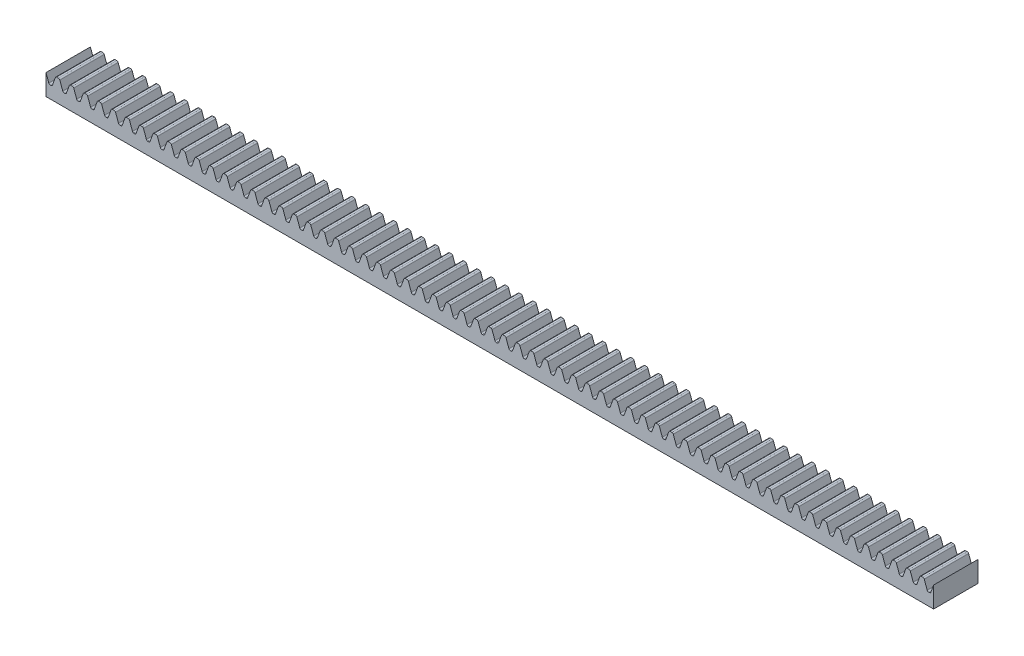
SolidWorks part; units mm, degrees
ref_plane "Front Plane" through (0, 0, 0) normal (0, 0, 1) x (1, 0, 0)
ref_plane "Top Plane" through (0, 0, 0) normal (0, 1, 0) x (1, 0, 0)
ref_plane "Right Plane" through (0, 0, 0) normal (1, 0, 0) x (0, 0, -1)
sketch "Sketch1" plane through (0, 0, 0) normal (0, 0, 1) x (1, 0, 0)
  line L0 (-50, 6) -> (-50, -6) construction
  line L1 (-50, -6) -> (50, -6) construction
  line L2 (50, -6) -> (50, 6) construction
  line L4 (0, 6) -> (0, -6) construction
  line L5 (-50, 5.5) -> (50, 5.5) construction
  line L6 (-48.9054, 6) -> (-48.484, 6) construction
  line L7 (-48.484, 6) -> (-48.0745, 4.875) construction
  line L8 (-48.9054, 6) -> (-49.3149, 4.875) construction
  line L9 (-49.3149, 4.875) -> (-48.0745, 4.875) construction
  line L10 (-48.6947, 6) -> (-48.6947, 4.875) construction
  line L11 (-50, 0) -> (-45.5531, 0) construction
  line L12 (50, 0) -> (45.5531, 0) construction
  point P15 (-47.1239, 6)
  point P16 (-31.5, -6)
  point P17 (-48.302, 5.5)
  point P18 (-49.0874, 5.5)
  point P21 (-0.25, -6)
  dimension "Length" = 100
  dimension "Height" = 12
  dimension "Approximate Number of Teeth" = 63
  dimension "Pressure Angle" = 20
  dimension "Circular Pitch" = 1.5708
  dimension "Addendum" = 0.5
  dimension "Dedendum" = 0.625
  dimension "Circular Tooth Thickness" = 0.7854
  dimension "Module" = 0.5
  dimension "Rack Length" = 97.3894
  dimension "D1" = 3.1416
sketch "Sketch2" plane through (0, 0, 0) normal (1, 0, 0) x (0, 0, -1)
  line L0 (-2.5, 0) -> (2.5, 0) construction
  dimension "Face Width" = 5
sketch "Sketch3" plane through (0, 0, 0) normal (0, 0, 1) x (1, 0, 0)
  line L1 (-50, 6) -> (50, 6)
  line L2 (-50, 6) -> (-50, -6)
  line L3 (-50, -6) -> (50, -6)
  line L4 (50, 6) -> (50, -6)
extrude "Boss-Extrude1" add sketch "Sketch3" against normal up to vertex (2.5 mm away) and the other way up to vertex (2.5 mm away) up to point (0, 0, -2.5) other way up to point (0, 0, 2.5)
sketch "Sketch4" plane through (0, 0, 0) normal (0, 0, 1) x (1, 0, 0)
  line L0 (-48.6947, 6) -> (-47.1239, 6) construction
  line L9 (-47.9093, 6) -> (-47.9093, 4.875)
  line L10 (-47.9093, 4.875) -> (-48.0745, 4.875)
  line L11 (-48.0745, 4.875) -> (-48.484, 6)
  line L12 (-48.484, 6) -> (-47.9093, 6)
  line L13 (-48.9054, 6) -> (-49.3149, 4.875)
  line L14 (-49.3149, 4.875) -> (-49.4801, 4.875)
  line L15 (-49.4801, 4.875) -> (-49.4801, 6)
  line L16 (-49.4801, 6) -> (-48.9054, 6)
  line L17 (50, 6) -> (-50, 6) construction
  line L18 (-48.9054, 6) -> (-48.7879, 6)
  line L19 (-48.6014, 6) -> (-48.484, 6)
  arc A0 (-49.4323, 4.875) -> (-49.2747, 4.9854) centre (-49.4323, 5.0428) ccw
  arc A1 (-48.1147, 4.9854) -> (-47.957, 4.875) centre (-47.957, 5.0428) ccw
  arc A2 (-48.9456, 5.8896) -> (-48.7879, 6) centre (-48.7879, 5.8322) cw
  arc A3 (-48.6014, 6) -> (-48.4438, 5.8896) centre (-48.6014, 5.8322) cw
  dimension "D1" = 0.1678
extrude "Cut-Extrude1" cut sketch "Sketch4" against normal through all both and the other way through all contours L14 A0 L13 L16 L15 | L13 A2 L18 | L19 A3 L11 | L11 A1 L10 L9 L12
pattern_linear "LPattern1" count 64 spacing 1.5708 along (1, 0, 0) count 2 spacing 1.5708 along (-1, 0, 0) of "Cut-Extrude1"
sketch "Drawing Refernce 1" plane through (0, 0, 2.5) normal (0, 0, 1) x (1, 0, 0)
  line L0 (-50, 0) -> (50, 0) construction
  point P6 (-35, 0)
  point P7 (-27.5, 0)
  point P8 (35, 0)
  dimension "D1" = 15
  dimension "D2" = 22.5
  dimension "D3" = 15
sketch "Sketch5" plane through (0, 0, 2.5) normal (0, 0, 1) x (1, 0, 0)
  line L0 (50, -6) -> (50, 5.8495) construction
  line L1 (-50, -6) -> (50, -6)
  line L2 (-50, -6) -> (-50, 3.5)
  line L3 (-50, 3.5) -> (50, 3.5)
  line L4 (50, -6) -> (50, 3.5)
  dimension "D1" = 2.5
extrude "Cut-Extrude2" cut sketch "Sketch5" against normal through all
equation "\"Diametral Pitch\"= 1 / \"Module\""
equation "\"Pressure Angle\"=20"
equation "\"Dedendum\"= 1.25 / \"Diametral Pitch\""
equation "\"Addendum\"= 1 / \"Diametral Pitch\""
equation "\"WorkingDepth\"= 2 / \"Diametral Pitch\""
equation "\"WholeDepth\"= 2.25 / \"Diametral Pitch\""
equation "\"Clearance\"= 0.25 / \"Diametral Pitch\""
equation "\"ToothThickness\"= ( pi / 2 ) / \"Diametral Pitch\""
equation "\"CircularPitch\"= pi / \"Diametral Pitch\""
equation "\"Fillet\"= \"Clearance\" * cos ( \"Pressure Angle\" ) * tan ( ( 90 + \"Pressure Angle\" ) / 2 )"
equation "\"Module\"= 0.5"
equation "\"Addendum@Sketch1\"=\"Addendum\""
equation "\"Pressure Angle@Sketch1\"=\"Pressure Angle\""
equation "\"Dedendum@Sketch1\"=\"Dedendum\""
equation "\"Circular Pitch@Sketch1\"=\"CircularPitch\""
equation "\"Circular Tooth Thickness@Sketch1\"=\"ToothThickness\""
equation "\"Module@Sketch1\"=\"Module\""
equation "\"Approximate Number of Teeth@Sketch1\" = int ( \"Length@Sketch1\" /  ( 2 * \"Circular Tooth Thickness@Sketch1\" )  ) "
equation "\"Rack Length@Sketch1\" = \"Circular Pitch@Sketch1\" *  ( \"Approximate Number of Teeth@Sketch1\" - 1 ) "
equation "\"D3@LPattern1\"=\"CircularPitch\""
equation "\"D1@LPattern1\"=\"Approximate Number of Teeth@Sketch1\"+1"
equation "\"D1@Sketch1\"=\"Circular Pitch@Sketch1\"*2"
equation "\"D1@Sketch4\"=\"Fillet\""
equation "\"D4@LPattern1\"=\"CircularPitch\""
equation "\"D2@Drawing Refernce 1\"=\"D1@Drawing Refernce 1\"*1.5"
equation "\"D3@Drawing Refernce 1\"=\"D1@Drawing Refernce 1\""
